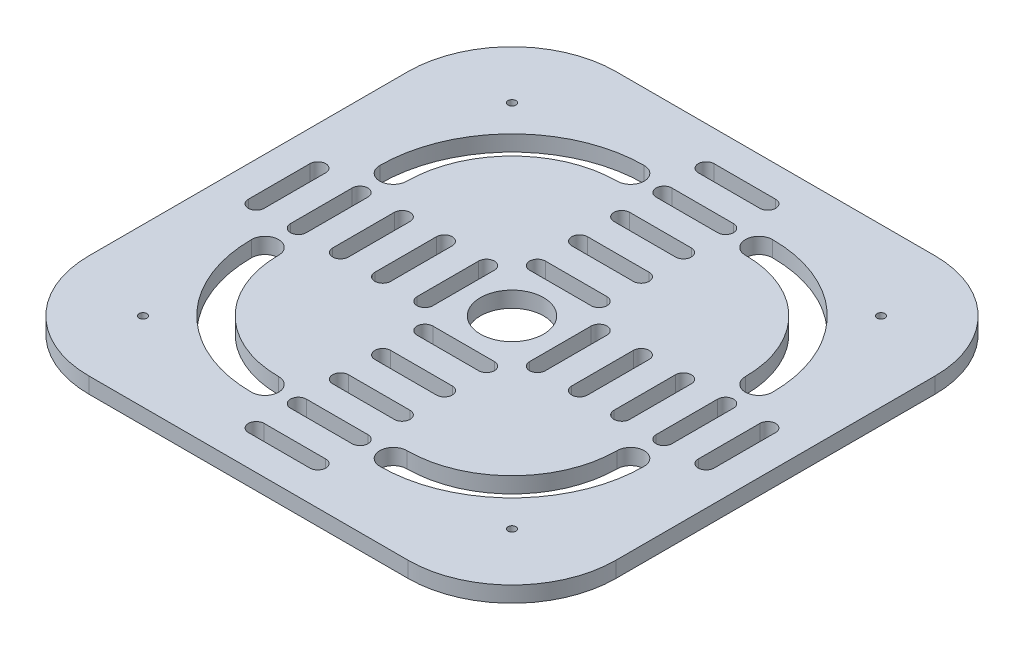
SolidWorks part; units mm, degrees
material "ABS"
ref_plane "Ön Düzlem" through (0, 0, 0) normal (0, 0, 1) x (1, 0, 0)
ref_plane "Üst Düzlem" through (0, 0, 0) normal (0, 1, 0) x (1, 0, 0)
ref_plane "Sağ Düzlem" through (0, 0, 0) normal (1, 0, 0) x (0, 0, -1)
sketch "Çizim1" plane through (0, 0, 0) normal (0, 1, 0) x (1, 0, 0)
  line L5 (0, 35) -> (0, -35) construction
  line L6 (-35, 0) -> (35, 0) construction
  line L7 (-50, -50) -> (50, -50)
  line L8 (-50, -50) -> (-50, 50)
  line L9 (-50, 50) -> (50, 50)
  line L10 (50, -50) -> (50, 50)
  line L11 (0, 50) -> (0, -50) construction
  line L12 (-50, 0) -> (50, 0) construction
  circle A0 centre (-35, 35) radius 0.75
  circle A1 centre (35, 35) radius 0.75
  circle A2 centre (35, -35) radius 0.75
  circle A3 centre (-35, -35) radius 0.75
  point P0 (0, 0)
  point P4 (0, 0)
  point P18 (0, 0)
  dimension "D3" = 4
extrude "Yükseklik-Ekstrüzyon1" add sketch "Çizim1" against normal blind 3
sketch "Çizim2" plane through (0, 0, 0) normal (0, 1, 0) x (1, 0, 0)
  circle A0 centre (0, 0) radius 6
extrude "Kes-Ekstrüzyon1" cut sketch "Çizim2" against normal blind 4 contours A0
sketch "Çizim3" plane through (0, 0, 0) normal (0, 1, 0) x (1, 0, 0)
  line L0 (-50, 30.2637) -> (-50, 50)
  line L1 (-50, 50) -> (-30.2637, 50)
  line L2 (50, 50) -> (50, 30.2637)
  line L3 (30.2637, 50) -> (50, 50)
  line L4 (50, -50) -> (30.2637, -50)
  line L5 (50, -30.2637) -> (50, -50)
  line L6 (-50, -50) -> (-50, -30.2637)
  line L7 (-30.2637, -50) -> (-50, -50)
  arc A0 (50, 30.2637) -> (30.2637, 50) centre (30.2637, 30.2637) ccw
  arc A1 (30.2637, -50) -> (50, -30.2637) centre (30.2637, -30.2637) ccw
  arc A2 (-50, -30.2637) -> (-30.2637, -50) centre (-30.2637, -30.2637) ccw
  arc A3 (-30.2637, 50) -> (-50, 30.2637) centre (-30.2637, 30.2637) ccw
  point P11 (0, 0)
  point P24 (0, 0)
  dimension "D1" = 4
  dimension "D2" = 4
extrude "Kes-Ekstrüzyon2" cut sketch "Çizim3" against normal blind 4
sketch "Çizim4" plane through (0, 0, 0) normal (0, 1, 0) x (1, 0, 0)
  line L0 (-55.2056, 0) -> (58.6821, 0) construction
  line L1 (0, 54.5799) -> (0, -55.1361) construction
  line L2 (-10.6747, -5.8414) -> (-10.6747, 5.8414)
  line L3 (-10.6747, 5.8414) -> (-10.6747, -5.8414) construction
  line L4 (-9.1747, 5.8414) -> (-9.1747, -5.8414)
  line L5 (-12.1747, 5.8414) -> (-12.1747, -5.8414)
  line L6 (-18.6747, 5.8414) -> (-18.6747, -5.8414) construction
  line L7 (-17.1747, 5.8414) -> (-17.1747, -5.8414)
  line L8 (-20.1747, 5.8414) -> (-20.1747, -5.8414)
  line L9 (-26.6747, 5.8414) -> (-26.6747, -5.8414) construction
  line L10 (-25.1747, 5.8414) -> (-25.1747, -5.8414)
  line L11 (-28.1747, 5.8414) -> (-28.1747, -5.8414)
  line L12 (-34.6747, 5.8414) -> (-34.6747, -5.8414) construction
  line L13 (-33.1747, 5.8414) -> (-33.1747, -5.8414)
  line L14 (-36.1747, 5.8414) -> (-36.1747, -5.8414)
  line L15 (-42.6747, 5.8414) -> (-42.6747, -5.8414) construction
  line L16 (-41.1747, 5.8414) -> (-41.1747, -5.8414)
  line L17 (-44.1747, 5.8414) -> (-44.1747, -5.8414)
  line L18 (-5.8414, 10.6747) -> (5.8414, 10.6747)
  line L19 (5.8414, 10.6747) -> (-5.8414, 10.6747) construction
  line L20 (5.8414, 9.1747) -> (-5.8414, 9.1747)
  line L21 (5.8414, 12.1747) -> (-5.8414, 12.1747)
  line L22 (5.8414, 18.6747) -> (-5.8414, 18.6747) construction
  line L23 (5.8414, 17.1747) -> (-5.8414, 17.1747)
  line L24 (5.8414, 20.1747) -> (-5.8414, 20.1747)
  line L25 (5.8414, 26.6747) -> (-5.8414, 26.6747) construction
  line L26 (5.8414, 25.1747) -> (-5.8414, 25.1747)
  line L27 (5.8414, 28.1747) -> (-5.8414, 28.1747)
  line L28 (5.8414, 34.6747) -> (-5.8414, 34.6747) construction
  line L29 (5.8414, 33.1747) -> (-5.8414, 33.1747)
  line L30 (5.8414, 36.1747) -> (-5.8414, 36.1747)
  line L31 (5.8414, 42.6747) -> (-5.8414, 42.6747) construction
  line L32 (5.8414, 41.1747) -> (-5.8414, 41.1747)
  line L33 (5.8414, 44.1747) -> (-5.8414, 44.1747)
  line L34 (10.6747, 5.8414) -> (10.6747, -5.8414)
  line L35 (10.6747, -5.8414) -> (10.6747, 5.8414) construction
  line L36 (9.1747, -5.8414) -> (9.1747, 5.8414)
  line L37 (12.1747, -5.8414) -> (12.1747, 5.8414)
  line L38 (18.6747, -5.8414) -> (18.6747, 5.8414) construction
  line L39 (17.1747, -5.8414) -> (17.1747, 5.8414)
  line L40 (20.1747, -5.8414) -> (20.1747, 5.8414)
  line L41 (26.6747, -5.8414) -> (26.6747, 5.8414) construction
  line L42 (25.1747, -5.8414) -> (25.1747, 5.8414)
  line L43 (28.1747, -5.8414) -> (28.1747, 5.8414)
  line L44 (34.6747, -5.8414) -> (34.6747, 5.8414) construction
  line L45 (33.1747, -5.8414) -> (33.1747, 5.8414)
  line L46 (36.1747, -5.8414) -> (36.1747, 5.8414)
  line L47 (42.6747, -5.8414) -> (42.6747, 5.8414) construction
  line L48 (41.1747, -5.8414) -> (41.1747, 5.8414)
  line L49 (44.1747, -5.8414) -> (44.1747, 5.8414)
  line L50 (5.8414, -10.6747) -> (-5.8414, -10.6747)
  line L51 (-5.8414, -10.6747) -> (5.8414, -10.6747) construction
  line L52 (-5.8414, -9.1747) -> (5.8414, -9.1747)
  line L53 (-5.8414, -12.1747) -> (5.8414, -12.1747)
  line L54 (-5.8414, -18.6747) -> (5.8414, -18.6747) construction
  line L55 (-5.8414, -17.1747) -> (5.8414, -17.1747)
  line L56 (-5.8414, -20.1747) -> (5.8414, -20.1747)
  line L57 (-5.8414, -26.6747) -> (5.8414, -26.6747) construction
  line L58 (-5.8414, -25.1747) -> (5.8414, -25.1747)
  line L59 (-5.8414, -28.1747) -> (5.8414, -28.1747)
  line L60 (-5.8414, -34.6747) -> (5.8414, -34.6747) construction
  line L61 (-5.8414, -33.1747) -> (5.8414, -33.1747)
  line L62 (-5.8414, -36.1747) -> (5.8414, -36.1747)
  line L63 (-5.8414, -42.6747) -> (5.8414, -42.6747) construction
  line L64 (-5.8414, -41.1747) -> (5.8414, -41.1747)
  line L65 (-5.8414, -44.1747) -> (5.8414, -44.1747)
  arc A0 (-9.1747, 5.8414) -> (-12.1747, 5.8414) centre (-10.6747, 5.8414) ccw
  arc A1 (-12.1747, -5.8414) -> (-9.1747, -5.8414) centre (-10.6747, -5.8414) ccw
  arc A2 (-17.1747, 5.8414) -> (-20.1747, 5.8414) centre (-18.6747, 5.8414) ccw
  arc A3 (-20.1747, -5.8414) -> (-17.1747, -5.8414) centre (-18.6747, -5.8414) ccw
  arc A4 (-25.1747, 5.8414) -> (-28.1747, 5.8414) centre (-26.6747, 5.8414) ccw
  arc A5 (-28.1747, -5.8414) -> (-25.1747, -5.8414) centre (-26.6747, -5.8414) ccw
  arc A6 (-33.1747, 5.8414) -> (-36.1747, 5.8414) centre (-34.6747, 5.8414) ccw
  arc A7 (-36.1747, -5.8414) -> (-33.1747, -5.8414) centre (-34.6747, -5.8414) ccw
  arc A8 (-41.1747, 5.8414) -> (-44.1747, 5.8414) centre (-42.6747, 5.8414) ccw
  arc A9 (-44.1747, -5.8414) -> (-41.1747, -5.8414) centre (-42.6747, -5.8414) ccw
  arc A10 (5.8414, 9.1747) -> (5.8414, 12.1747) centre (5.8414, 10.6747) ccw
  arc A11 (-5.8414, 12.1747) -> (-5.8414, 9.1747) centre (-5.8414, 10.6747) ccw
  arc A12 (5.8414, 17.1747) -> (5.8414, 20.1747) centre (5.8414, 18.6747) ccw
  arc A13 (-5.8414, 20.1747) -> (-5.8414, 17.1747) centre (-5.8414, 18.6747) ccw
  arc A14 (5.8414, 25.1747) -> (5.8414, 28.1747) centre (5.8414, 26.6747) ccw
  arc A15 (-5.8414, 28.1747) -> (-5.8414, 25.1747) centre (-5.8414, 26.6747) ccw
  arc A16 (5.8414, 33.1747) -> (5.8414, 36.1747) centre (5.8414, 34.6747) ccw
  arc A17 (-5.8414, 36.1747) -> (-5.8414, 33.1747) centre (-5.8414, 34.6747) ccw
  arc A18 (5.8414, 41.1747) -> (5.8414, 44.1747) centre (5.8414, 42.6747) ccw
  arc A19 (-5.8414, 44.1747) -> (-5.8414, 41.1747) centre (-5.8414, 42.6747) ccw
  arc A20 (9.1747, -5.8414) -> (12.1747, -5.8414) centre (10.6747, -5.8414) ccw
  arc A21 (12.1747, 5.8414) -> (9.1747, 5.8414) centre (10.6747, 5.8414) ccw
  arc A22 (17.1747, -5.8414) -> (20.1747, -5.8414) centre (18.6747, -5.8414) ccw
  arc A23 (20.1747, 5.8414) -> (17.1747, 5.8414) centre (18.6747, 5.8414) ccw
  arc A24 (25.1747, -5.8414) -> (28.1747, -5.8414) centre (26.6747, -5.8414) ccw
  arc A25 (28.1747, 5.8414) -> (25.1747, 5.8414) centre (26.6747, 5.8414) ccw
  arc A26 (33.1747, -5.8414) -> (36.1747, -5.8414) centre (34.6747, -5.8414) ccw
  arc A27 (36.1747, 5.8414) -> (33.1747, 5.8414) centre (34.6747, 5.8414) ccw
  arc A28 (41.1747, -5.8414) -> (44.1747, -5.8414) centre (42.6747, -5.8414) ccw
  arc A29 (44.1747, 5.8414) -> (41.1747, 5.8414) centre (42.6747, 5.8414) ccw
  arc A30 (-5.8414, -9.1747) -> (-5.8414, -12.1747) centre (-5.8414, -10.6747) ccw
  arc A31 (5.8414, -12.1747) -> (5.8414, -9.1747) centre (5.8414, -10.6747) ccw
  arc A32 (-5.8414, -17.1747) -> (-5.8414, -20.1747) centre (-5.8414, -18.6747) ccw
  arc A33 (5.8414, -20.1747) -> (5.8414, -17.1747) centre (5.8414, -18.6747) ccw
  arc A34 (-5.8414, -25.1747) -> (-5.8414, -28.1747) centre (-5.8414, -26.6747) ccw
  arc A35 (5.8414, -28.1747) -> (5.8414, -25.1747) centre (5.8414, -26.6747) ccw
  arc A36 (-5.8414, -33.1747) -> (-5.8414, -36.1747) centre (-5.8414, -34.6747) ccw
  arc A37 (5.8414, -36.1747) -> (5.8414, -33.1747) centre (5.8414, -34.6747) ccw
  arc A38 (-5.8414, -41.1747) -> (-5.8414, -44.1747) centre (-5.8414, -42.6747) ccw
  arc A39 (5.8414, -44.1747) -> (5.8414, -41.1747) centre (5.8414, -42.6747) ccw
  arc A40 (-34.6747, 12.1747) -> (-12.1747, 34.6747) centre (-12.1747, 12.1747) cw construction
  arc A41 (-12.1747, 37.2497) -> (-37.2497, 12.1747) centre (-12.1747, 12.1747) ccw
  arc A42 (-12.1747, 32.0997) -> (-32.0997, 12.1747) centre (-12.1747, 12.1747) ccw
  arc A43 (-12.1747, 32.0997) -> (-12.1747, 37.2497) centre (-12.1747, 34.6747) ccw
  arc A44 (-37.2497, 12.1747) -> (-32.0997, 12.1747) centre (-34.6747, 12.1747) ccw
  arc A45 (12.1747, 34.6747) -> (34.6747, 12.1747) centre (12.1747, 12.1747) cw construction
  arc A46 (37.2497, 12.1747) -> (12.1747, 37.2497) centre (12.1747, 12.1747) ccw
  arc A47 (32.0997, 12.1747) -> (12.1747, 32.0997) centre (12.1747, 12.1747) ccw
  arc A48 (32.0997, 12.1747) -> (37.2497, 12.1747) centre (34.6747, 12.1747) ccw
  arc A49 (12.1747, 37.2497) -> (12.1747, 32.0997) centre (12.1747, 34.6747) ccw
  arc A50 (34.6747, -12.1747) -> (12.1747, -34.6747) centre (12.1747, -12.1747) cw construction
  arc A51 (12.1747, -37.2497) -> (37.2497, -12.1747) centre (12.1747, -12.1747) ccw
  arc A52 (12.1747, -32.0997) -> (32.0997, -12.1747) centre (12.1747, -12.1747) ccw
  arc A53 (12.1747, -32.0997) -> (12.1747, -37.2497) centre (12.1747, -34.6747) ccw
  arc A54 (37.2497, -12.1747) -> (32.0997, -12.1747) centre (34.6747, -12.1747) ccw
  arc A55 (-12.1747, -34.6747) -> (-34.6747, -12.1747) centre (-12.1747, -12.1747) cw construction
  arc A56 (-37.2497, -12.1747) -> (-12.1747, -37.2497) centre (-12.1747, -12.1747) ccw
  arc A57 (-32.0997, -12.1747) -> (-12.1747, -32.0997) centre (-12.1747, -12.1747) ccw
  arc A58 (-32.0997, -12.1747) -> (-37.2497, -12.1747) centre (-34.6747, -12.1747) ccw
  arc A59 (-12.1747, -37.2497) -> (-12.1747, -32.0997) centre (-12.1747, -34.6747) ccw
  point P5 (-10.6747, 0)
  point P8 (-10.6747, 0)
  point P14 (0, 10.6747)
  point P15 (-18.6747, 0)
  point P22 (-26.6747, 0)
  point P29 (-34.6747, 0)
  point P36 (-42.6747, 0)
  point P47 (0, 10.6747)
  point P52 (0, 18.6747)
  point P59 (0, 26.6747)
  point P66 (0, 34.6747)
  point P73 (0, 42.6747)
  point P80 (10.6747, 0)
  point P83 (10.6747, 0)
  point P88 (18.6747, 0)
  point P95 (26.6747, 0)
  point P102 (34.6747, 0)
  point P109 (42.6747, 0)
  point P116 (0, -10.6747)
  point P119 (0, -10.6747)
  point P124 (0, -18.6747)
  point P131 (0, -26.6747)
  point P138 (0, -34.6747)
  point P145 (0, -42.6747)
  point P152 (0, 0)
  point P153 (-28.0846, 28.0846)
  point P164 (28.0846, 28.0846)
  point P172 (28.0846, -28.0846)
  point P180 (-28.0846, -28.0846)
  point P185 (0, 0)
  dimension "D1" = 5
  dimension "D2" = 4
  dimension "D3" = 4
extrude "Kes-Ekstrüzyon3" cut sketch "Çizim4" against normal blind 4
